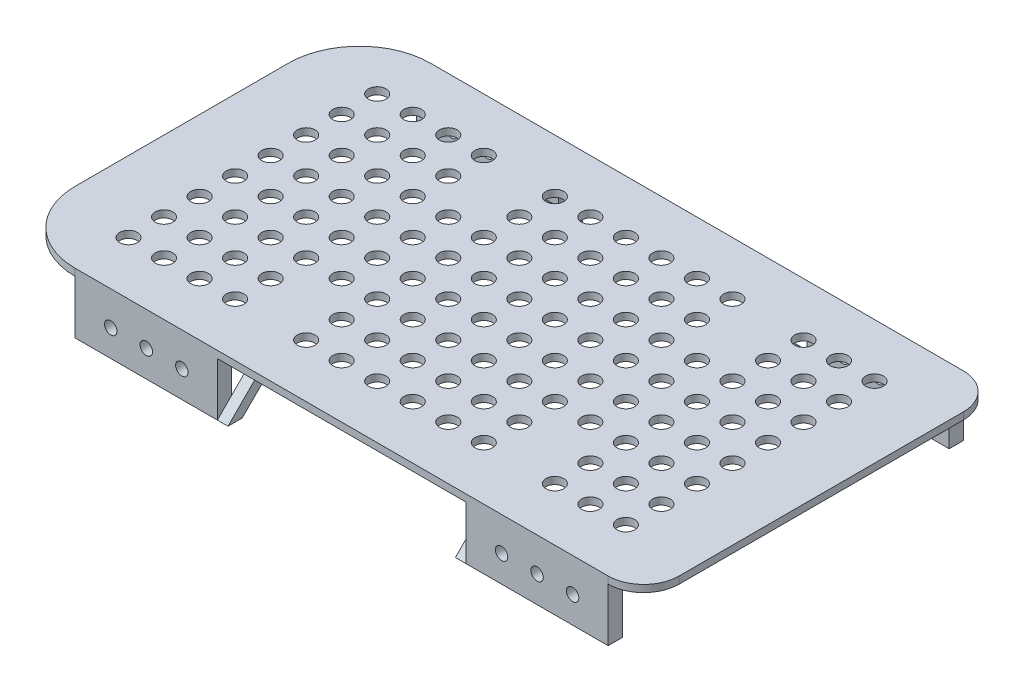
SolidWorks part; units mm, degrees
ref_plane "Ön Düzlem" through (0, 0, 0) normal (0, 0, 1) x (1, 0, 0)
ref_plane "Üst Düzlem" through (0, 0, 0) normal (0, 1, 0) x (1, 0, 0)
ref_plane "Sağ Düzlem" through (0, 0, 0) normal (1, 0, 0) x (0, 0, -1)
sketch "Çizim1" plane through (0, 0, 0) normal (0, 1, 0) x (1, 0, 0)
  line L1 (-70, -50) -> (80, -50)
  line L2 (-90, -30) -> (-90, 30)
  line L3 (-70, 50) -> (80, 50)
  line L4 (90, -40) -> (90, 40)
  line L5 (-90, -50) -> (90, 50) construction
  line L6 (-90, 50) -> (90, -50) construction
  arc A0 (-70, -50) -> (-90, -30) centre (-70, -30) cw
  arc A1 (-90, 30) -> (-70, 50) centre (-70, 30) cw
  arc A2 (80, -50) -> (90, -40) centre (80, -40) ccw
  arc A3 (80, 50) -> (90, 40) centre (80, 40) cw
  point P0 (0, 0)
  dimension "D1" = 20
  dimension "D2" = 10
  dimension "D3" = 180
  dimension "D4" = 100
extrude "Yükseklik-Ekstrüzyon1" add sketch "Çizim1" along normal blind 2
sketch "Çizim3" plane through (0, 0, 0) normal (0, -1, 0) x (1, 0, 0)
  line L0 (-70, 50) -> (-70, 46)
  line L1 (-70, 46) -> (-30, 46)
  line L2 (-30, 46) -> (-30, 50)
  line L3 (-70, 50) -> (80, 50) construction
  line L4 (-30, 50) -> (-70, 50)
  line L5 (80, 50) -> (40, 50)
  line L6 (40, 50) -> (40, 46)
  line L7 (40, 46) -> (80, 46)
  line L8 (80, 46) -> (80, 50)
  line L9 (-70, -50) -> (-70, -46)
  line L10 (-70, -46) -> (-30, -46)
  line L11 (-30, -46) -> (-30, -50)
  line L12 (80, -50) -> (-70, -50) construction
  line L13 (-30, -50) -> (-70, -50)
  line L14 (80, -50) -> (80, -46)
  line L15 (80, -46) -> (40, -46)
  line L16 (40, -46) -> (40, -50)
  line L17 (40, -50) -> (80, -50)
  line L18 (-90, -30) -> (-90, 30) construction
  line L19 (90, 40) -> (90, -40) construction
  point P27 (40, -48)
  dimension "D1" = 40
  dimension "D2" = 4
  dimension "D3" = 20
  dimension "D4" = 70
  dimension "D5" = 10
  dimension "D6" = 92
extrude "Yükseklik-Ekstrüzyon2" add sketch "Çizim3" along normal blind 15
sketch "Çizim4" plane through (-30, 0, 0) normal (1, 0, 0) x (0, 0, -1)
  line L0 (50, -15) -> (46, -15)
  line L1 (46, -15) -> (31, 0)
  line L2 (-40, 0) -> (40, 0) construction
  line L3 (31, 0) -> (35, 0)
  line L4 (35, 0) -> (50, -15)
  line L6 (-35, 0) -> (-50, -15)
  line L7 (-31, 0) -> (-35, 0)
  line L8 (-46, -15) -> (-31, 0)
  line L9 (-50, -15) -> (-46, -15)
extrude "Yükseklik-Ekstrüzyon3" add sketch "Çizim4" along normal blind 3
sketch "Çizim5" plane through (40, 0, 0) normal (-1, 0, 0) x (0, 0, 1)
  line L0 (-50, -15) -> (-46, -15)
  line L1 (-46, -15) -> (-31, 0)
  line L2 (-31, 0) -> (-35, 0)
  line L3 (-35, 0) -> (-50, -15)
  line L5 (35, 0) -> (50, -15)
  line L6 (31, 0) -> (35, 0)
  line L7 (46, -15) -> (31, 0)
  line L8 (50, -15) -> (46, -15)
extrude "Yükseklik-Ekstrüzyon4" add sketch "Çizim5" along normal blind 3
sketch "Çizim6" plane through (0, 0, 50) normal (0, 0, 1) x (1, 0, 0)
  circle A0 centre (-60, -7.5) radius 1.75
  circle A1 centre (-50, -7.5) radius 1.75
  circle A3 centre (-40, -7.5) radius 1.75
  circle A4 centre (50, -7.5) radius 1.75
  circle A5 centre (60, -7.5) radius 1.75
  circle A6 centre (70, -7.5) radius 1.75
extrude "Kes-Ekstrüzyon1" cut sketch "Çizim6" against normal blind 101
sketch "Çizim7" plane through (0, 2, 0) normal (0, 1, 0) x (1, 0, 0)
  circle A0 centre (-70, 35) radius 2.5
  circle A1 centre (-70, 25) radius 2.5
  circle A2 centre (-70, 15) radius 2.5
  circle A3 centre (-70, 5) radius 2.5
  circle A4 centre (-70, -5) radius 2.5
  circle A5 centre (-70, -15) radius 2.5
  circle A6 centre (-70, -25) radius 2.5
  circle A7 centre (-70, -35) radius 2.5
  circle A8 centre (-60, -35) radius 2.5
  circle A9 centre (-60, -25) radius 2.5
  circle A10 centre (-60, -15) radius 2.5
  circle A11 centre (-60, -5) radius 2.5
  circle A12 centre (-60, 5) radius 2.5
  circle A13 centre (-60, 15) radius 2.5
  circle A14 centre (-60, 25) radius 2.5
  circle A15 centre (-60, 35) radius 2.5
  circle A16 centre (-50, 35) radius 2.5
  circle A17 centre (-50, 25) radius 2.5
  circle A18 centre (-50, 15) radius 2.5
  circle A19 centre (-50, 5) radius 2.5
  circle A20 centre (-50, -5) radius 2.5
  circle A21 centre (-50, -15) radius 2.5
  circle A22 centre (-50, -25) radius 2.5
  circle A23 centre (-50, -35) radius 2.5
  circle A24 centre (-40, -35) radius 2.5
  circle A25 centre (-40, -25) radius 2.5
  circle A26 centre (-40, -15) radius 2.5
  circle A27 centre (-40, -5) radius 2.5
  circle A28 centre (-40, 5) radius 2.5
  circle A29 centre (-40, 15) radius 2.5
  circle A30 centre (-40, 25) radius 2.5
  circle A31 centre (-40, 35) radius 2.5
  circle A35 centre (-30, 5) radius 2.5
  circle A36 centre (-30, -5) radius 2.5
  circle A37 centre (-30, -15) radius 2.5
  circle A40 centre (-20, -35) radius 2.5
  circle A41 centre (-20, -25) radius 2.5
  circle A42 centre (-20, -15) radius 2.5
  circle A43 centre (-20, -5) radius 2.5
  circle A44 centre (-20, 5) radius 2.5
  circle A45 centre (-10, 5) radius 2.5
  circle A46 centre (-10, -5) radius 2.5
  circle A47 centre (-10, -15) radius 2.5
  circle A48 centre (-10, -25) radius 2.5
  circle A49 centre (-10, -35) radius 2.5
  circle A52 centre (-30, 15) radius 2.5
  circle A53 centre (-20, 15) radius 2.5
  circle A54 centre (-20, 25) radius 2.5
  circle A55 centre (-20, 35) radius 2.5
  circle A56 centre (-10, 35) radius 2.5
  circle A57 centre (-10, 25) radius 2.5
  circle A58 centre (-10, 15) radius 2.5
  circle A59 centre (0, 15) radius 2.5
  circle A60 centre (0, 25) radius 2.5
  circle A61 centre (0, 35) radius 2.5
  circle A62 centre (10, 35) radius 2.5
  circle A63 centre (10, 25) radius 2.5
  circle A64 centre (10, 15) radius 2.5
  circle A65 centre (20, 15) radius 2.5
  circle A66 centre (20, 25) radius 2.5
  circle A67 centre (20, 35) radius 2.5
  circle A68 centre (0, -35) radius 2.5
  circle A69 centre (0, -25) radius 2.5
  circle A70 centre (0, -15) radius 2.5
  circle A71 centre (0, -5) radius 2.5
  circle A72 centre (0, 5) radius 2.5
  circle A73 centre (10, 5) radius 2.5
  circle A74 centre (10, -5) radius 2.5
  circle A75 centre (10, -15) radius 2.5
  circle A76 centre (10, -25) radius 2.5
  circle A77 centre (10, -35) radius 2.5
  circle A78 centre (20, -35) radius 2.5
  circle A79 centre (20, -25) radius 2.5
  circle A80 centre (20, -15) radius 2.5
  circle A81 centre (20, -5) radius 2.5
  circle A82 centre (20, 5) radius 2.5
  circle A83 centre (30, 35) radius 2.5
  circle A84 centre (30, 25) radius 2.5
  circle A85 centre (30, 15) radius 2.5
  circle A86 centre (30, 5) radius 2.5
  circle A87 centre (30, -5) radius 2.5
  circle A88 centre (30, -15) radius 2.5
  circle A89 centre (30, -25) radius 2.5
  circle A90 centre (30, -35) radius 2.5
  circle A93 centre (40, -15) radius 2.5
  circle A94 centre (40, -5) radius 2.5
  circle A95 centre (40, 5) radius 2.5
  circle A96 centre (40, 15) radius 2.5
  circle A99 centre (50, 35) radius 2.5
  circle A100 centre (50, 25) radius 2.5
  circle A101 centre (50, 15) radius 2.5
  circle A102 centre (50, 5) radius 2.5
  circle A103 centre (50, -5) radius 2.5
  circle A104 centre (50, -15) radius 2.5
  circle A105 centre (50, -25) radius 2.5
  circle A106 centre (50, -35) radius 2.5
  circle A107 centre (60, -35) radius 2.5
  circle A108 centre (60, -25) radius 2.5
  circle A109 centre (60, -15) radius 2.5
  circle A110 centre (60, -5) radius 2.5
  circle A111 centre (60, 5) radius 2.5
  circle A112 centre (60, 15) radius 2.5
  circle A113 centre (60, 25) radius 2.5
  circle A114 centre (60, 35) radius 2.5
  circle A115 centre (70, 35) radius 2.5
  circle A116 centre (70, 25) radius 2.5
  circle A117 centre (70, 15) radius 2.5
  circle A118 centre (70, 5) radius 2.5
  circle A119 centre (70, -5) radius 2.5
  circle A120 centre (70, -15) radius 2.5
  circle A121 centre (70, -25) radius 2.5
  circle A122 centre (70, -35) radius 2.5
extrude "Kes-Ekstrüzyon2" cut sketch "Çizim7" against normal blind 2
